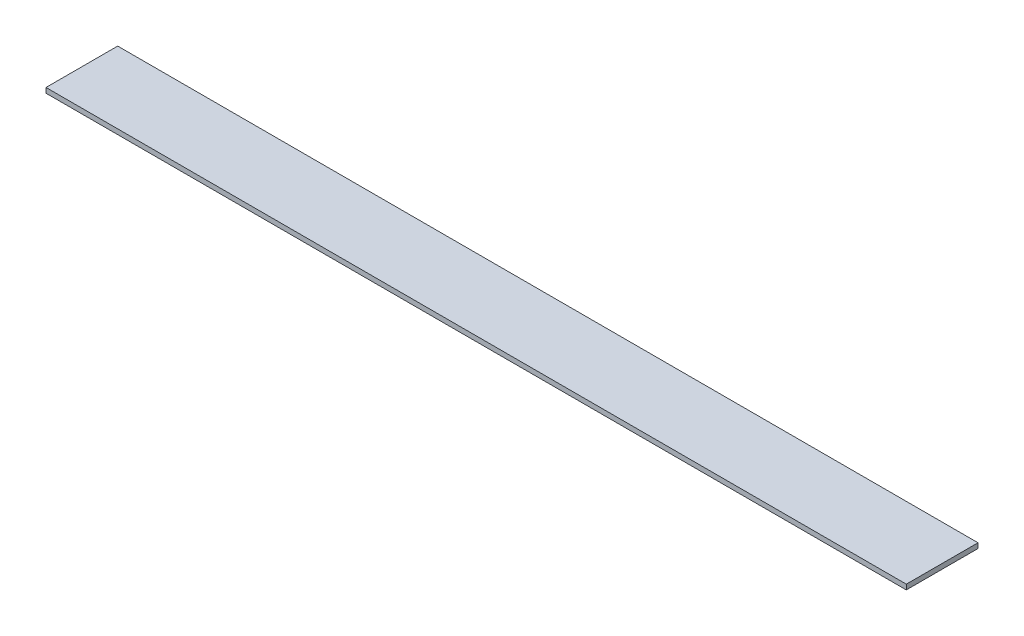
SolidWorks part; units mm, degrees
ref_plane "Front Plane" through (0, 0, 0) normal (0, 0, 1) x (1, 0, 0)
ref_plane "Top Plane" through (0, 0, 0) normal (0, 1, 0) x (1, 0, 0)
ref_plane "Right Plane" through (0, 0, 0) normal (1, 0, 0) x (0, 0, -1)
sketch "Sketch1" plane through (0, 0, 0) normal (0, 1, 0) x (1, 0, 0)
  line L1 (-60, -5) -> (60, -5)
  line L2 (-60, -5) -> (-60, 5)
  line L3 (-60, 5) -> (60, 5)
  line L4 (60, -5) -> (60, 5)
  line L5 (-60, -5) -> (60, 5) construction
  line L6 (-60, 5) -> (60, -5) construction
  point P0 (0, 0)
  dimension "D1" = 10
  dimension "D2" = 120
extrude "Boss-Extrude1" add sketch "Sketch1" along normal blind 0.7
